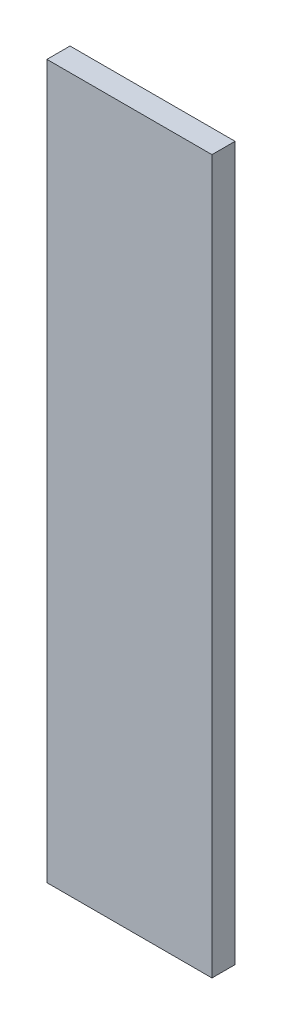
SolidWorks part; units mm, degrees
ref_plane "Front Plane" through (0, 0, 0) normal (0, 0, 1) x (1, 0, 0)
ref_plane "Top Plane" through (0, 0, 0) normal (0, 1, 0) x (1, 0, 0)
ref_plane "Right Plane" through (0, 0, 0) normal (1, 0, 0) x (0, 0, -1)
sketch "Sketch1" plane through (0, 0, 0) normal (0, 0, 1) x (1, 0, 0)
  line L0 (1700, 550) -> (1700, 1630)
  line L1 (1700, 1630) -> (1950, 1630)
  line L2 (1950, 1630) -> (1950, 550)
  line L3 (1950, 550) -> (1700, 550)
extrude "Boss-Extrude1" add sketch "Sketch1" along normal blind 35
